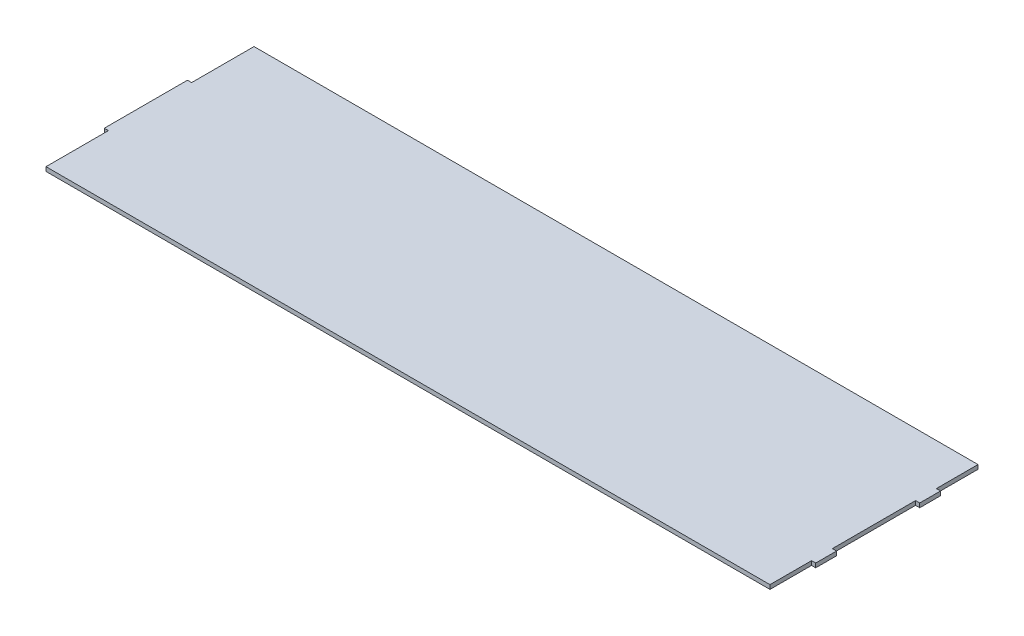
SolidWorks part; units mm, degrees
ref_plane "前视基准面" through (0, 0, 0) normal (0, 0, 1) x (1, 0, 0)
ref_plane "上视基准面" through (0, 0, 0) normal (0, 1, 0) x (1, 0, 0)
ref_plane "右视基准面" through (0, 0, 0) normal (1, 0, 0) x (0, 0, -1)
sketch "草图1" plane through (0, 0, 0) normal (0, 1, 0) x (1, 0, 0)
  line L0 (0, 0) -> (0, 100)
  line L1 (0, 0) -> (348, 0)
  line L2 (0, 100) -> (348, 100)
  line L3 (348, 0) -> (348, 100)
  line L4 (0, 30) -> (-2, 30)
  line L5 (0, 30) -> (0, 70)
  line L6 (-2, 30) -> (-2, 70)
  line L7 (0, 70) -> (-2, 70)
  line L8 (348, 80) -> (350, 80)
  line L9 (348, 80) -> (348, 70)
  line L10 (350, 80) -> (350, 70)
  line L11 (348, 70) -> (350, 70)
  line L14 (348, 30) -> (350, 30)
  line L15 (348, 30) -> (348, 20)
  line L16 (350, 30) -> (350, 20)
  line L17 (348, 20) -> (350, 20)
  point P0 (0, 0)
extrude "凸台-拉伸1" add sketch "草图1" along normal blind 2 contours L17 L3 L14 L16 | L3 L11 L10 L8 | L1 L3 L2 L0 | L0 L7 L6 L4
